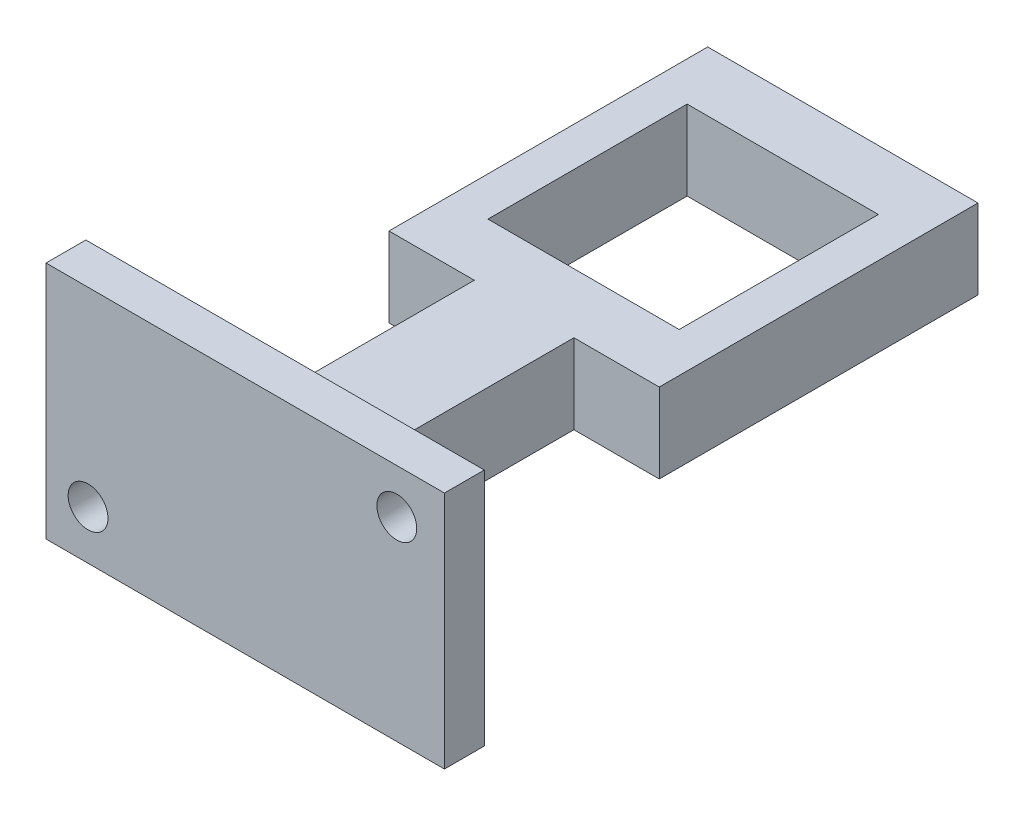
SolidWorks part; units mm, degrees
ref_plane "Front Plane" through (0, 0, 0) normal (0, 0, 1) x (1, 0, 0)
ref_plane "Top Plane" through (0, 0, 0) normal (0, 1, 0) x (1, 0, 0)
ref_plane "Right Plane" through (0, 0, 0) normal (1, 0, 0) x (0, 0, -1)
sketch "Sketch1" plane through (0, 0, 0) normal (0, 0, 1) x (1, 0, 0)
  line L1 (-25, -15) -> (25, -15)
  line L2 (-25, -15) -> (-25, 15)
  line L3 (-25, 15) -> (25, 15)
  line L4 (25, -15) -> (25, 15)
  line L5 (-25, -15) -> (25, 15) construction
  line L6 (-25, 15) -> (25, -15) construction
  point P0 (0, 0)
  dimension "D1" = 30
  dimension "D2" = 50
extrude "Boss-Extrude1" add sketch "Sketch1" along normal blind 5
sketch "Sketch2" plane through (0, 0, 0) normal (0, 1, 0) x (1, 0, 0)
  line L0 (-6.2502, 30) -> (-6.2502, 0)
  line L2 (-6.2502, 0) -> (6.2502, 0)
  line L3 (6.2502, 30) -> (6.2502, 0)
  line L4 (-6.2502, 30) -> (6.2502, 0) construction
  line L5 (-6.2502, 0) -> (6.2502, 30) construction
  line L6 (-16.9589, 70) -> (-16.9589, 30)
  line L7 (-16.9589, 70) -> (16.9589, 70)
  line L8 (-16.9589, 30) -> (-6.2502, 30)
  line L9 (16.9589, 70) -> (16.9589, 30)
  line L10 (-16.9589, 70) -> (16.9589, 30) construction
  line L11 (-16.9589, 30) -> (16.9589, 70) construction
  line L12 (6.2502, 30) -> (16.9589, 30)
  point P1 (0, 15)
  point P2 (0, 50)
  dimension "D1" = 12.5004
  dimension "D2" = 30
  dimension "D3" = 33.9177
  dimension "D4" = 40
extrude "Boss-Extrude2" add sketch "Sketch2" along normal blind 5 and the other way blind 5 contours L9 L12 L3 L2 L0 L8 L6 L7
sketch "Sketch3" plane through (0, 5, 0) normal (0, 1, 0) x (1, 0, 0)
  line L0 (-12.0411, 37.5) -> (11.9589, 37.5)
  line L1 (-12.0411, 37.5) -> (-12.0411, 62.5)
  line L2 (11.9589, 37.5) -> (11.9589, 62.5)
  line L3 (-12.0411, 62.5) -> (11.9589, 62.5)
  line L4 (-12.0411, 37.5) -> (11.9589, 62.5) construction
  line L5 (11.9589, 37.5) -> (-12.0411, 62.5) construction
  line L6 (16.9589, 70) -> (16.9589, 30) construction
  line L7 (-16.9589, 30) -> (-6.2502, 30) construction
  point P1 (-0.0411, 50)
  dimension "D1" = 25
  dimension "D2" = 24
  dimension "D3" = 5
  dimension "D4" = 7.5
extrude "Cut-Extrude1" cut sketch "Sketch3" against normal blind 10 contours L2 L3 L1 L0
sketch "Sketch4" plane through (0, 0, 0) normal (0, 0, -1) x (-1, 0, 0)
  circle A0 centre (-19.02, 9.4022) radius 2.5
  circle A1 centre (20.3131, -10.5337) radius 2.5
extrude "Cut-Extrude2" cut sketch "Sketch4" against normal blind 10 contours A0
sketch "Sketch5" plane through (0, 0, 0) normal (0, 0, -1) x (-1, 0, 0)
  circle A0 centre (19.7205, -8.8634) radius 2.5
extrude "Cut-Extrude3" cut sketch "Sketch5" against normal blind 10 contours A0
